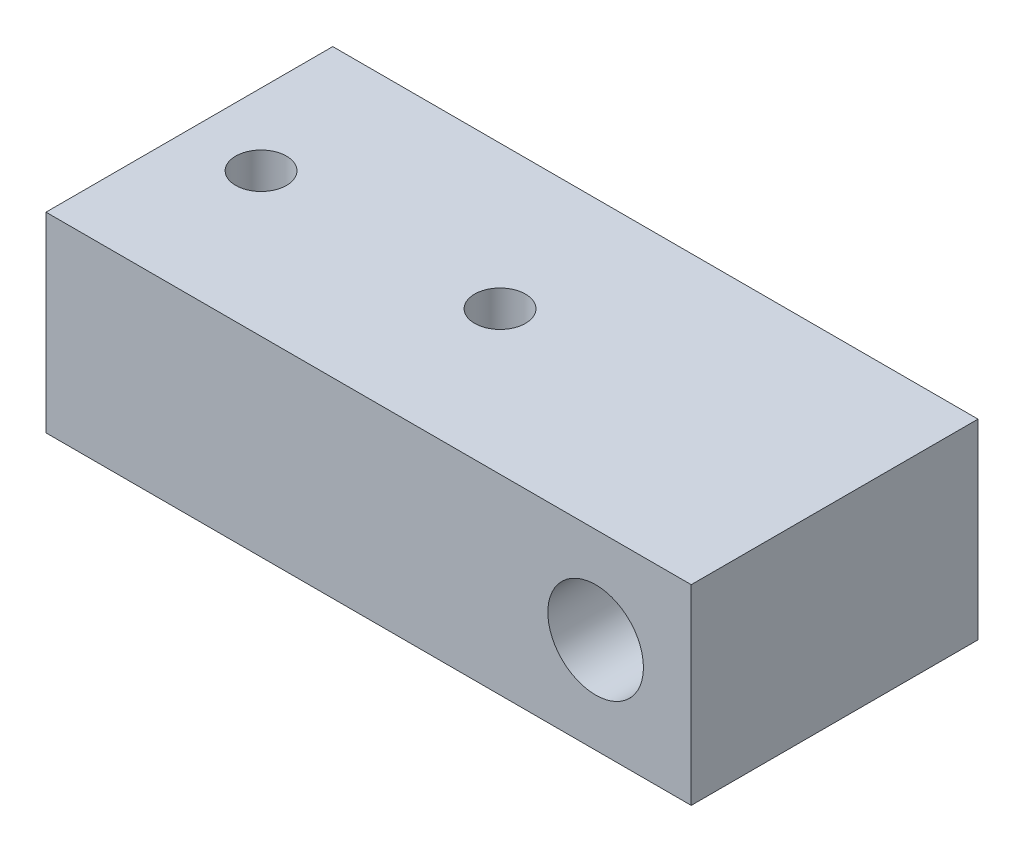
SolidWorks part; units mm, degrees
material "Plain Carbon Steel"
ref_plane "Front Plane" through (0, 0, 0) normal (0, 0, 1) x (1, 0, 0)
ref_plane "Top Plane" through (0, 0, 0) normal (0, 1, 0) x (1, 0, 0)
ref_plane "Right Plane" through (0, 0, 0) normal (1, 0, 0) x (0, 0, -1)
sketch "Sketch1" plane through (0, 0, 0) normal (0, 1, 0) x (1, 0, 0)
  line L1 (-42.8625, 19.05) -> (42.8625, 19.05)
  line L2 (-42.8625, 19.05) -> (-42.8625, -19.05)
  line L3 (-42.8625, -19.05) -> (42.8625, -19.05)
  line L4 (42.8625, 19.05) -> (42.8625, -19.05)
  line L5 (-42.8625, 19.05) -> (42.8625, -19.05) construction
  line L6 (-42.8625, -19.05) -> (42.8625, 19.05) construction
  point P0 (0, 0)
  dimension "D1" = 85.725
  dimension "D2" = 38.1
extrude "Boss-Extrude1" add sketch "Sketch1" along normal mid plane 25.4
hole_wizard "1/2 (0.5) Diameter Hole1" positions "Sketch2" profile "Sketch3" hole size "1/2" standard "ANSI Inch" end condition through all
sketch "Sketch2" plane through (0, 0, 19.05) normal (0, 0, 1) x (1, 0, 0)
  line L0 (-42.8625, -12.7) -> (42.8625, -12.7) construction
  line L1 (42.8625, 12.7) -> (42.8625, -12.7) construction
  line L2 (-42.8625, 12.7) -> (-42.8625, -12.7) construction
  point P0 (30.1625, 0)
  dimension "D1" = 12.7
  dimension "D2" = 12.7
  dimension "D3" = 73.025
sketch "Sketch3" plane through (30.1625, 0, 19.05) normal (1, 0, 0) x (0, -1, 0)
  line L0 (0, 0) -> (0, 38.1)
  line L1 (0, 38.1) -> (6.35, 38.1)
  line L2 (6.35, 38.1) -> (6.35, 0)
  line L5 (6.35, 0) -> (0, 0)
  line L11 (0, -6.35) -> (0, 107.95) construction
  dimension "Thru Hole Dia." = 12.7
  dimension "Thru Hole Depth" = 38.1
hole_wizard "1/4 Clearance Hole1" positions "Sketch4" profile "Sketch5" hole size "1/4" standard "ANSI Inch" end condition through all
sketch "Sketch4" plane through (0, 12.7, 0) normal (0, 1, 0) x (1, 0, 0)
  line L0 (42.8625, 19.05) -> (-42.8625, 19.05) construction
  line L3 (42.8625, -19.05) -> (42.8625, 19.05) construction
  point P0 (-33.3375, 0)
  point P2 (-1.5875, 0)
  dimension "D1" = 19.05
  dimension "D2" = 31.75
  dimension "D3" = 44.45
sketch "Sketch5" plane through (-33.3375, 12.7, 0) normal (1, 0, 0) x (0, 0, 1)
  line L0 (0, 0) -> (0, 25.4)
  line L1 (0, 25.4) -> (3.3782, 25.4)
  line L2 (3.3782, 25.4) -> (3.3782, 0)
  line L5 (3.3782, 0) -> (0, 0)
  line L11 (0, -6.35) -> (0, 107.95) construction
  dimension "Thru Hole Dia." = 6.7564
  dimension "Thru Hole Depth" = 25.4
sketch "Sketch6" plane through (0, 0, -19.05) normal (0, 0, -1) x (-1, 0, 0)
  line L0 (-159.1006, -55.2481) -> (-14.1596, -8.1539) construction
  line L1 (-159.1006, -55.2481) -> (-166.9496, -31.0913) construction
  line L2 (-14.1596, -8.1539) -> (-22.0086, 16.0029) construction
  line L3 (-166.9496, -31.0913) -> (-22.0086, 16.0029) construction
  line L4 (-42.8625, -12.7) -> (42.8625, -12.7) construction
  line L5 (-42.8625, 12.7) -> (-42.8625, 8.7191)
  line L6 (-42.8625, 12.7) -> (-42.8625, -12.7) construction
  line L7 (-42.8625, 8.7191) -> (-29.6545, 12.7)
  line L8 (-42.8625, 12.7) -> (42.8625, 12.7) construction
  line L9 (-29.6545, 12.7) -> (-42.8625, 12.7)
  circle A0 centre (-30.1625, 0) radius 6.35 construction
  point P0 (-30.1625, 0)
  point P21 (-42.8625, 9.2271)
  dimension "D1" = 152.4
  dimension "D2" = 25.4
  dimension "D3" = 12.7
  dimension "D4" = 12.7
  dimension "D5" = 18
  dimension "D6" = 0.508
  dimension "D7" = 0.508
extrude "Cut-Extrude1" [suppressed] cut sketch "Sketch6" against normal through all contours L9 L5 L7
